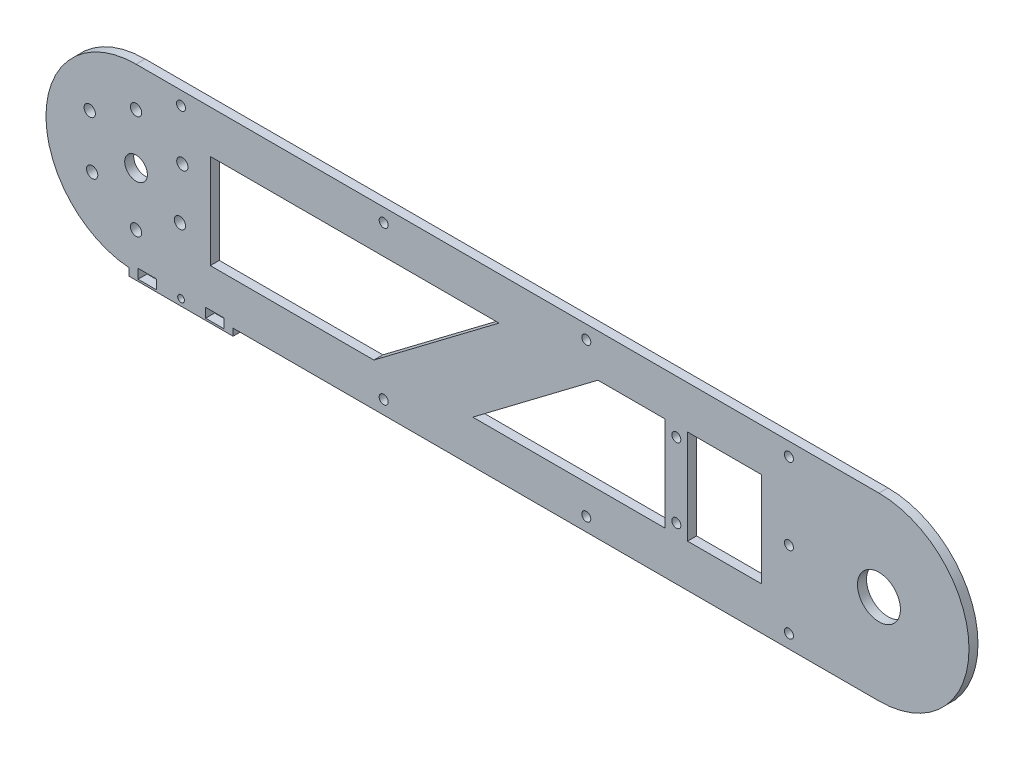
SolidWorks part; units mm, degrees
ref_plane "前视基准面" through (0, 0, 0) normal (0, 0, 1) x (1, 0, 0)
ref_plane "上视基准面" through (0, 0, 0) normal (0, 1, 0) x (1, 0, 0)
ref_plane "右视基准面" through (0, 0, 0) normal (1, 0, 0) x (0, 0, -1)
sketch "草图1" plane through (0, 0, 0) normal (0, 0, 1) x (1, 0, 0)
  line L0 (-1.4571, -0.1457) -> (37.8152, -22.8196) construction
  line L1 (-1.4571, -0.1457) -> (328.5429, -0.1457) construction
  line L3 (-1.4571, -40.1457) -> (328.5429, -40.1457)
  line L8 (-1.4571, 39.8543) -> (328.5429, 39.8543)
  circle A0 centre (-1.4571, -0.1457) radius 23.75 construction
  circle A1 centre (-1.4571, -0.1457) radius 22.5 construction
  circle A2 centre (-1.4571, -23.8957) radius 2.5
  circle A3 centre (18.0284, -11.3957) radius 2.5
  circle A4 centre (-1.4571, -0.1457) radius 40 construction
  circle A6 centre (-1.4571, -0.1457) radius 5.03
  circle A12 centre (328.5429, -0.1457) radius 40 construction
  arc A16 (-1.4571, -40.1457) -> (-1.4571, 39.8543) centre (-1.4571, -0.1457) cw
  circle A17 centre (-22.0252, 11.7293) radius 2.5
  circle A18 centre (-20.9427, -11.3957) radius 2.5
  circle A19 centre (19.111, 11.7293) radius 2.5
  circle A20 centre (-1.4571, 22.3543) radius 2.5
  arc A21 (328.5429, -40.1457) -> (328.5429, 39.8543) centre (328.5429, -0.1457) ccw
  circle A22 centre (328.5429, -0.1457) radius 9.53
  circle A23 centre (288.5429, -0.1457) radius 2
  circle A24 centre (238.5429, 16.3543) radius 2
  circle A25 centre (238.5429, -16.6457) radius 2
  dimension "D1" = 45
  dimension "D2" = 3
  dimension "D3" = 5
  dimension "D4" = 19.06
  dimension "D5" = 80
  dimension "D6" = 80
  dimension "D7" = 10.06
  dimension "D11" = 4
  dimension "D8" = 330
  dimension "D9" = 50
  dimension "D10" = 16.5
extrude "凸台-拉伸1" add sketch "草图1" along normal blind 4 contours L3
sketch "草图3" plane through (0, 0, 4) normal (0, 0, 1) x (1, 0, 0)
  line L1 (41.6429, -39.4527) -> (-4.5571, -39.4527)
  line L2 (41.6429, -39.4527) -> (41.6429, -43.2699)
  line L3 (41.6429, -43.2699) -> (-4.5571, -43.2699)
  line L4 (-4.5571, -39.4527) -> (-4.5571, -43.2699)
  line L7 (-1.4571, -40.1457) -> (328.5429, -40.1457) construction
  dimension "D1" = 3.1
  dimension "D2" = 46.2
  dimension "D3" = 3.1242
extrude "凸台-拉伸2" add sketch "草图3" against normal blind 4
sketch "草图2" plane through (0, 0, 4) normal (0, 0, 1) x (1, 0, 0)
  line L0 (18.5429, 33.8543) -> (198.5429, 33.8543) construction
  line L1 (108.5429, -34.1457) -> (198.5429, 33.8543) construction
  line L2 (18.5429, 33.8543) -> (18.5429, -34.1457) construction
  line L3 (18.5429, -34.1457) -> (108.5429, -34.1457) construction
  line L4 (31.5429, -21.1457) -> (104.1839, -21.1457)
  line L5 (104.1839, -21.1457) -> (159.7721, 20.8543)
  line L6 (31.5429, 20.8543) -> (159.7721, 20.8543)
  line L7 (31.5429, 20.8543) -> (31.5429, -21.1457)
  line L8 (108.5429, -34.1457) -> (288.5429, -34.1457) construction
  line L9 (288.5429, -34.1457) -> (288.5429, 33.8543) construction
  line L10 (288.5429, 33.8543) -> (198.5429, 33.8543) construction
  line L11 (276.3527, 20.8543) -> (203.7117, 20.8543) construction
  line L12 (148.1234, -21.1457) -> (203.7117, 20.8543)
  line L13 (148.1234, -21.1457) -> (276.3527, -21.1457) construction
  line L14 (276.3527, -21.1457) -> (276.3527, 20.8543)
  line L15 (233.5429, 20.8543) -> (233.5429, -21.1457)
  line L16 (243.5429, 20.8543) -> (243.5429, -21.1457)
  line L17 (238.5429, 16.3543) -> (238.5429, -16.6457) construction
  line L18 (233.5429, 20.8543) -> (203.7117, 20.8543)
  line L19 (243.5429, 20.8543) -> (276.3527, 20.8543)
  line L20 (243.5429, -21.1457) -> (276.3527, -21.1457)
  line L21 (233.5429, -21.1457) -> (148.1234, -21.1457)
  line L22 (41.6429, -40.1457) -> (328.5429, -40.1457) construction
  line L27 (18.5429, -34.1457) -> (18.5429, -40.1457) construction
  line L28 (41.6429, -40.1457) -> (328.5429, -40.1457) construction
  line L29 (29.4429, -38.2299) -> (37.6429, -38.2299)
  line L30 (29.4429, -38.2299) -> (29.4429, -42.4299)
  line L31 (29.4429, -42.4299) -> (37.6429, -42.4299)
  line L32 (37.6429, -38.2299) -> (37.6429, -42.4299)
  line L33 (29.4429, -38.2299) -> (37.6429, -42.4299) construction
  line L34 (29.4429, -42.4299) -> (37.6429, -38.2299) construction
  line L35 (-0.5571, -38.2299) -> (7.6429, -38.2299)
  line L36 (-0.5571, -38.2299) -> (-0.5571, -42.4299)
  line L37 (-0.5571, -42.4299) -> (7.6429, -42.4299)
  line L38 (7.6429, -38.2299) -> (7.6429, -42.4299)
  line L39 (-0.5571, -38.2299) -> (7.6429, -42.4299) construction
  line L40 (-0.5571, -42.4299) -> (7.6429, -38.2299) construction
  line L41 (-4.5571, -43.2699) -> (41.6429, -43.2699) construction
  circle A0 centre (18.5429, 33.8543) radius 2
  circle A1 centre (108.5429, 33.8543) radius 2
  circle A2 centre (198.5429, 33.8543) radius 2
  circle A3 centre (288.5429, 33.8543) radius 2
  circle A4 centre (108.5429, -34.1457) radius 2
  circle A5 centre (198.5429, -34.1457) radius 2
  circle A6 centre (288.5429, -34.1457) radius 2
  arc A8 (-1.4571, 39.8543) -> (-4.5571, -40.0254) centre (-1.4571, -0.1457) ccw construction
  circle A9 centre (18.5429, -40.3299) radius 1.5
  point P2 (-1.4571, -0.1457)
  point P40 (33.5429, -40.3299)
  point P45 (0, 0)
  point P46 (3.5429, -40.3299)
  point P53 (0, 0)
  dimension "D1" = 4
  dimension "D6" = 15
  dimension "D12" = 3
  dimension "D14" = 68
  dimension "D2" = 34
  dimension "D3" = 20
  dimension "D4" = 10
  dimension "D5" = 20
  dimension "D7" = 8.2
  dimension "D8" = 4.2
  dimension "D9" = 15
  dimension "D10" = 8.2
  dimension "D11" = 4.2
  dimension "D13" = 6
  dimension "D15" = 2.94
extrude "切除-拉伸1" cut sketch "草图2" against normal blind 4
